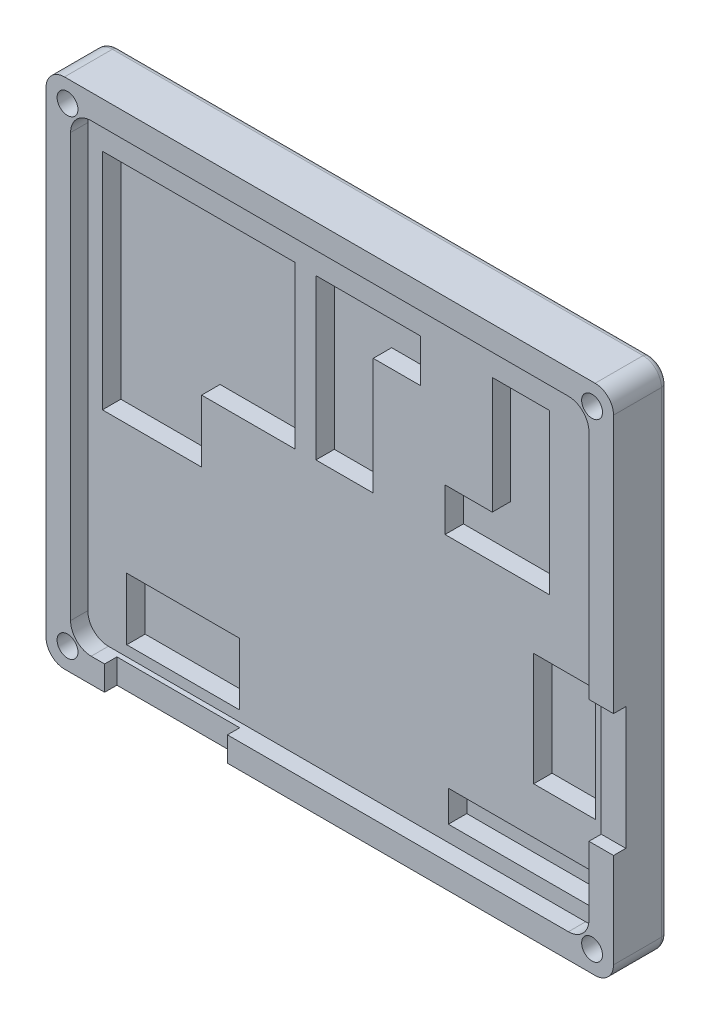
SolidWorks part; units mm, degrees
ref_plane "Front" through (0, 0, 0) normal (0, 0, 1) x (1, 0, 0)
ref_plane "Top" through (0, 0, 0) normal (0, 1, 0) x (1, 0, 0)
ref_plane "Right" through (0, 0, 0) normal (1, 0, 0) x (0, 0, -1)
sketch "Sketch1" plane through (0, 0, 0) normal (0, 0, 1) x (1, 0, 0)
  line L0 (-19.431, 20.8825) -> (19.431, 20.8825)
  line L1 (-19.431, -18.8825) -> (19.431, -18.8825)
  line L2 (-21.105, -17.2085) -> (-21.105, 17.2085)
  line L3 (-19.431, 18.8825) -> (19.431, 18.8825)
  line L4 (21.105, -17.2085) -> (21.105, 17.2085)
  line L5 (-21.105, -18.8825) -> (21.105, 18.8825) construction
  line L6 (-21.105, 18.8825) -> (21.105, -18.8825) construction
  line L7 (23.105, -17.2085) -> (23.105, 17.2085)
  line L8 (-19.431, -20.8825) -> (19.431, -20.8825)
  line L9 (-23.105, -17.2085) -> (-23.105, 17.2085)
  arc A0 (-19.431, -18.8825) -> (-21.105, -17.2085) centre (-19.431, -17.2085) cw
  arc A1 (19.431, -18.8825) -> (21.105, -17.2085) centre (19.431, -17.2085) ccw
  arc A2 (19.431, 18.8825) -> (21.105, 17.2085) centre (19.431, 17.2085) cw
  arc A3 (-21.105, 17.2085) -> (-19.431, 18.8825) centre (-19.431, 17.2085) cw
  arc A4 (19.431, 20.8825) -> (23.105, 17.2085) centre (19.431, 17.2085) cw
  arc A5 (19.431, -20.8825) -> (23.105, -17.2085) centre (19.431, -17.2085) ccw
  arc A6 (-19.431, -20.8825) -> (-23.105, -17.2085) centre (-19.431, -17.2085) cw
  arc A7 (-23.105, 17.2085) -> (-19.431, 20.8825) centre (-19.431, 17.2085) cw
  point P0 (0, 0)
  dimension "D1" = 1.674
  dimension "D3" = 37.765
  dimension "D4" = 42.21
  dimension "D2" = 2
extrude "Boss-Extrude1" add sketch "Sketch1" along normal blind 4.4
sketch "Sketch2" plane through (0, 0, 0) normal (0, 0, -1) x (-1, 0, 0)
  line L0 (-19.431, 18.8825) -> (19.431, 18.8825) construction
  line L1 (21.105, 17.2085) -> (21.105, -17.2085) construction
  line L2 (19.431, -18.8825) -> (-19.431, -18.8825) construction
  line L3 (-21.105, -17.2085) -> (-21.105, 17.2085) construction
  line L4 (21.105, 17.2085) -> (21.105, -17.2085)
  line L5 (19.431, -18.8825) -> (-19.431, -18.8825)
  line L6 (-21.105, -17.2085) -> (-21.105, 17.2085)
  line L7 (-19.431, 18.8825) -> (19.431, 18.8825)
  arc A0 (19.431, -18.8825) -> (21.105, -17.2085) centre (19.431, -17.2085) ccw construction
  arc A1 (-21.105, -17.2085) -> (-19.431, -18.8825) centre (-19.431, -17.2085) ccw construction
  arc A2 (-19.431, 18.8825) -> (-21.105, 17.2085) centre (-19.431, 17.2085) ccw construction
  arc A3 (21.105, 17.2085) -> (19.431, 18.8825) centre (19.431, 17.2085) ccw construction
  arc A4 (19.431, -18.8825) -> (21.105, -17.2085) centre (19.431, -17.2085) ccw
  arc A5 (-21.105, -17.2085) -> (-19.431, -18.8825) centre (-19.431, -17.2085) ccw
  arc A6 (-19.431, 18.8825) -> (-21.105, 17.2085) centre (-19.431, 17.2085) ccw
  arc A7 (21.105, 17.2085) -> (19.431, 18.8825) centre (19.431, 17.2085) ccw
extrude "Boss-Extrude2" add sketch "Sketch2" against normal blind 1.5
sketch "Sketch6" plane through (0, 0, 1.5) normal (0, 0, 1) x (1, 0, 0)
  line L2 (12.9585, 13.9065) -> (12.8315, 13.9065)
  line L3 (12.8315, 13.3985) -> (12.9585, 13.3985)
  line L4 (12.9585, 13.9065) -> (12.8315, 13.9065)
  line L5 (12.8315, 13.3985) -> (12.9585, 13.3985)
  line L6 (15.4985, 5.0165) -> (15.3715, 5.0165)
  line L7 (15.3715, 4.5085) -> (15.4985, 4.5085)
  line L8 (15.4985, 5.0165) -> (15.3715, 5.0165)
  line L9 (15.3715, 4.5085) -> (15.4985, 4.5085)
  line L12 (20.9423, -17.2085) -> (20.9423, 17.2085)
  line L13 (19.431, 18.7198) -> (-19.431, 18.7198)
  line L14 (-20.9423, 17.2085) -> (-20.9423, -17.2085)
  line L15 (-19.431, -18.7198) -> (19.431, -18.7198)
  line L16 (20.9423, -17.2085) -> (20.9423, 17.2085)
  line L17 (19.431, 18.7198) -> (-19.431, 18.7198)
  line L18 (-20.9423, 17.2085) -> (-20.9423, -17.2085)
  line L19 (-19.431, -18.7198) -> (19.431, -18.7198)
  circle A1 centre (3.985, 14.2075) radius 0.8 construction
  circle A2 centre (3.985, 14.2075) radius 0.8
  circle A3 centre (9.985, 4.2075) radius 0.8 construction
  circle A4 centre (9.985, 4.2075) radius 0.8
  arc A7 (19.2511, -3.4176) -> (19.2511, -2.7176) centre (19.2511, -3.0676) ccw construction
  arc A8 (12.9585, 13.3985) -> (12.9585, 13.9065) centre (12.9585, 13.6525) ccw
  arc A9 (12.8315, 13.9065) -> (12.8315, 13.3985) centre (12.8315, 13.6525) ccw
  arc A10 (12.9585, 13.3985) -> (12.9585, 13.9065) centre (12.9585, 13.6525) ccw
  arc A11 (12.8315, 13.9065) -> (12.8315, 13.3985) centre (12.8315, 13.6525) ccw
  circle A12 centre (16.201, -4.2425) radius 0.35 construction
  arc A13 (15.4985, 4.5085) -> (15.4985, 5.0165) centre (15.4985, 4.7625) ccw
  arc A14 (15.3715, 5.0165) -> (15.3715, 4.5085) centre (15.3715, 4.7625) ccw
  arc A15 (15.4985, 4.5085) -> (15.4985, 5.0165) centre (15.4985, 4.7625) ccw
  arc A16 (15.3715, 5.0165) -> (15.3715, 4.5085) centre (15.3715, 4.7625) ccw
  circle A17 centre (16.201, -9.0925) radius 0.35 construction
  arc A18 (19.2511, -10.6174) -> (19.2511, -9.9174) centre (19.2511, -10.2674) ccw construction
  arc A19 (19.431, -18.7198) -> (20.9423, -17.2085) centre (19.431, -17.2085) ccw
  arc A20 (20.9423, 17.2085) -> (19.431, 18.7198) centre (19.431, 17.2085) ccw
  arc A21 (-19.431, 18.7198) -> (-20.9423, 17.2085) centre (-19.431, 17.2085) ccw
  arc A22 (-20.9423, -17.2085) -> (-19.431, -18.7198) centre (-19.431, -17.2085) ccw
  arc A23 (19.431, -18.7198) -> (20.9423, -17.2085) centre (19.431, -17.2085) ccw
  arc A24 (20.9423, 17.2085) -> (19.431, 18.7198) centre (19.431, 17.2085) ccw
  arc A25 (-19.431, 18.7198) -> (-20.9423, 17.2085) centre (-19.431, 17.2085) ccw
  arc A26 (-20.9423, -17.2085) -> (-19.431, -18.7198) centre (-19.431, -17.2085) ccw
  arc A27 (19.2511, -10.6174) -> (19.2511, -9.9174) centre (19.2511, -10.2674) ccw
  circle A28 centre (16.201, -9.0925) radius 0.35
  circle A29 centre (16.201, -4.2425) radius 0.35
  arc A30 (19.2511, -3.4176) -> (19.2511, -2.7176) centre (19.2511, -3.0676) ccw
  circle A31 centre (19.685, -16.3195) radius 0.55 construction
  circle A32 centre (9.525, -16.3195) radius 0.55 construction
  circle A33 centre (19.685, -16.3195) radius 0.55
  circle A34 centre (9.525, -16.3195) radius 0.55
  arc A35 (-17.285, -17.0286) -> (-16.5849, -17.0286) centre (-16.935, -17.0286) ccw construction
  circle A36 centre (-10.91, -13.9785) radius 0.35 construction
  circle A37 centre (-15.76, -13.9785) radius 0.35 construction
  arc A38 (-10.0851, -17.0286) -> (-9.3851, -17.0286) centre (-9.7351, -17.0286) ccw construction
  arc A39 (-10.0851, -17.0286) -> (-9.3851, -17.0286) centre (-9.7351, -17.0286) ccw
  arc A40 (-17.285, -17.0286) -> (-16.5849, -17.0286) centre (-16.935, -17.0286) ccw
  circle A41 centre (-15.76, -13.9785) radius 0.35
  circle A42 centre (-10.91, -13.9785) radius 0.35
  circle A43 centre (-5.715, 14.2875) radius 0.5 construction
  circle A44 centre (-5.715, 14.2875) radius 0.5
  circle A45 centre (-18.415, 14.2875) radius 0.5 construction
  circle A46 centre (-18.415, 14.2875) radius 0.5
  circle A47 centre (-5.715, 4.1275) radius 0.5 construction
  circle A48 centre (-5.715, 4.1275) radius 0.5
  circle A49 centre (-13.335, -0.9525) radius 0.5 construction
  circle A50 centre (-13.335, -0.9525) radius 0.5
  circle A51 centre (-18.415, -0.9525) radius 0.5 construction
  circle A52 centre (-18.415, -0.9525) radius 0.5
  dimension "D1" = 0
  dimension "D2" = 0
  dimension "D3" = 0
sketch "Sketch3" plane through (0, 0, 1.5) normal (0, 0, 1) x (1, 0, 0)
  line L0 (-19.431, 18.8825) -> (19.431, 18.8825) construction
  line L1 (-21.105, 18.8825) -> (21.105, 18.8825)
  line L2 (-21.105, 18.8825) -> (-21.105, -18.8825)
  line L3 (-21.105, -18.8825) -> (21.105, -18.8825)
  line L4 (21.105, 18.8825) -> (21.105, -18.8825)
  line L5 (-21.105, -17.2085) -> (-21.105, 17.2085) construction
  line L6 (19.431, -18.8825) -> (-19.431, -18.8825) construction
  line L7 (21.105, 17.2085) -> (21.105, -17.2085) construction
  line L8 (-19.915, 15.7875) -> (-4.215, 15.7875)
  line L9 (-4.215, 15.7875) -> (-4.215, 2.6275)
  line L10 (-4.215, 2.6275) -> (-11.835, 2.6275)
  line L11 (-11.835, 2.6275) -> (-11.835, -2.4525)
  line L12 (-11.835, -2.4525) -> (-19.915, -2.4525)
  line L13 (-19.915, -2.4525) -> (-19.915, 15.7875)
  line L14 (3.985, 14.2075) -> (9.985, 4.2075) construction
  line L15 (5.985, 15.7075) -> (5.985, 12.2075)
  line L16 (-2.5285, 2.7075) -> (16.4985, 2.7075) construction
  line L17 (-2.5285, 2.7075) -> (-2.5285, 15.7075)
  line L18 (-2.5285, 15.7075) -> (16.4985, 15.7075) construction
  line L19 (16.4985, 2.7075) -> (16.4985, 15.7075)
  line L20 (-2.5285, 2.7075) -> (16.4985, 15.7075) construction
  line L21 (-2.5285, 15.7075) -> (16.4985, 2.7075) construction
  line L22 (5.985, 12.2075) -> (2.1385, 12.2075)
  line L23 (2.1385, 12.2075) -> (2.1385, 2.7075)
  line L24 (2.1385, 2.7075) -> (-2.5285, 2.7075)
  line L25 (-2.5285, 15.7075) -> (5.985, 15.7075)
  line L26 (16.4985, 15.7075) -> (11.8315, 15.7075)
  line L27 (11.8315, 15.7075) -> (11.8315, 6.2075)
  line L28 (11.8315, 6.2075) -> (7.985, 6.2075)
  line L29 (7.985, 6.2075) -> (7.985, 2.7075)
  line L30 (7.985, 2.7075) -> (16.4985, 2.7075)
  line L31 (16.201, -4.2425) -> (16.201, -9.0925) construction
  line L32 (20.2511, -2.0676) -> (15.201, -2.0676)
  line L33 (20.2511, -2.0676) -> (20.2511, -11.2674)
  line L34 (20.2511, -11.2674) -> (15.201, -11.2674)
  line L35 (15.201, -2.0676) -> (15.201, -11.2674)
  line L36 (-17.935, -12.9785) -> (-8.7351, -12.9785)
  line L37 (-17.935, -12.9785) -> (-17.935, -18.0286)
  line L38 (-17.935, -18.0286) -> (-8.7351, -18.0286)
  line L39 (-8.7351, -12.9785) -> (-8.7351, -18.0286)
  line L40 (8.255, -15.0495) -> (20.955, -15.0495)
  line L41 (8.255, -15.0495) -> (8.255, -17.5895)
  line L42 (8.255, -17.5895) -> (20.955, -17.5895)
  line L43 (20.955, -15.0495) -> (20.955, -17.5895)
  line L44 (16.201, -6.6675) -> (20.2511, -6.6675) construction
  line L45 (-15.76, -13.9785) -> (-10.91, -13.9785) construction
  line L46 (-13.335, -13.9785) -> (-13.335, -12.9785) construction
  line L47 (9.525, -16.3195) -> (8.255, -16.3195) construction
  line L48 (9.525, -16.3195) -> (9.525, -15.0495) construction
  line L49 (19.685, -16.3195) -> (20.955, -16.3195) construction
  point P27 (6.985, 9.2075)
  point P32 (6.985, 9.2075)
  dimension "D1" = 1.5
  dimension "D2" = 1.5
  dimension "D3" = 1.5
  dimension "D4" = 1.5
  dimension "D5" = 1.5
  dimension "D6" = 1.5
  dimension "D7" = 1
  dimension "D8" = 1.5
  dimension "D9" = 2
  dimension "D10" = 2
  dimension "D11" = 1
  dimension "D12" = 1
  dimension "D13" = 1
  dimension "D14" = 1
  dimension "D15" = 1
  dimension "D16" = 1.27
extrude "Boss-Extrude3" add sketch "Sketch3" along normal blind 1.5
sketch "Sketch5" plane through (0, 0, 4.4) normal (0, 0, 1) x (1, 0, 0)
  line L0 (19.431, 20.8825) -> (21.605, 20.8825)
  line L1 (21.605, 20.8825) -> (23.105, 19.3825) construction
  line L2 (23.105, 19.3825) -> (23.105, 17.2085)
  arc A0 (23.105, 17.2085) -> (19.431, 20.8825) centre (19.431, 17.2085) ccw construction
  arc A1 (23.105, 17.2085) -> (19.431, 20.8825) centre (19.431, 17.2085) ccw
  arc A2 (21.605, 20.8825) -> (23.105, 19.3825) centre (21.605, 19.3825) cw
  dimension "D1" = 1.5
extrude "Boss-Extrude4" add sketch "Sketch5" against normal up to surface (4.4 mm away) up to face at (0, 0, 0)
sketch "Sketch4" plane through (0, 0, 4.4) normal (0, 0, 1) x (1, 0, 0)
  line L0 (19.431, 17.2085) -> (21.3572, 19.1347) construction
  line L1 (19.431, 18.8825) -> (-19.431, 18.8825) construction
  arc A0 (21.105, 17.2085) -> (19.431, 18.8825) centre (19.431, 17.2085) ccw construction
  circle A1 centre (21.3572, 19.1347) radius 0.85
  circle A2 centre (21.3572, 19.1347) radius 1.65 construction
  point P8 (20.6147, 18.3922)
  point P10 (20.7561, 18.5336)
  point P11 (22.9516, 20.883)
  dimension "D2" = 3.3
  dimension "D4" = 1.7
  dimension "D1" = 135
  dimension "D3" = 0.2
extrude "Cut-Extrude1" cut sketch "Sketch4" against normal through all
mirror "Mirror1" about plane through (0, 0, 0) normal (1, 0, 0) of "Boss-Extrude4", "Cut-Extrude1"
mirror "Mirror2" about plane through (0, 0, 0) normal (0, 1, 0) of "Mirror1", "Boss-Extrude4", "Cut-Extrude1"
fillet "Fillet1" radius 0.5 8 edges at (22.6657, 20.4432, 0) (23.105, 0, 0) (22.6657, -20.4432, 0) (0, -20.8825, 0) (-22.6657, -20.4432, 0) (-23.105, 0, 0) (-22.6657, 20.4432, 0) (0, 20.8825, 0)
sketch "Sketch7" plane through (0, -20.8825, 0) normal (0, -1, 0) x (1, 0, 0)
  line L0 (-21.605, 4.4) -> (21.605, 4.4) construction
  line L1 (-8.335, 4.4) -> (-18.335, 4.4)
  line L2 (-8.335, 4.4) -> (-8.335, 3.4)
  line L3 (-8.335, 3.4) -> (-18.335, 3.4)
  line L4 (-18.335, 4.4) -> (-18.335, 3.4)
  line L5 (-8.7351, 3) -> (-17.935, 3) construction
  line L6 (-8.7351, 3) -> (-17.935, 3) construction
  line L7 (-13.335, 3) -> (-13.335, 4.4) construction
  dimension "D1" = 1
  dimension "D2" = 10
extrude "Cut-Extrude2" cut sketch "Sketch7" against normal blind 3
sketch "Sketch8" plane through (23.105, 0, 0) normal (1, 0, 0) x (0, 0, -1)
  line L0 (-3, -2.0676) -> (-3, -11.2674) construction
  line L1 (-3, -2.0676) -> (-3, -11.2674) construction
  line L2 (-4.4, -19.3825) -> (-4.4, 19.3825) construction
  line L3 (-4.4, -1.6675) -> (-3.4, -1.6675)
  line L4 (-4.4, -1.6675) -> (-4.4, -11.6675)
  line L5 (-4.4, -11.6675) -> (-3.4, -11.6675)
  line L6 (-3.4, -1.6675) -> (-3.4, -11.6675)
  line L7 (-3, -6.6675) -> (-4.4, -6.6675) construction
  line L8 (-4.4, -20.8825) -> (-3.4, -20.8825) construction
  line L9 (-4.4, -20.8825) -> (-3.4, -20.8825) construction
  point P10 (0, 0)
  dimension "D1" = 10
extrude "Cut-Extrude3" cut sketch "Sketch8" against normal blind 3
equation "\"D3@Sketch1\"=1.475in+0.3mm"
equation "\"D4@Sketch1\"=1.65in+0.3mm"
equation "\"D1@Sketch1\"=0.06in+0.15mm"
